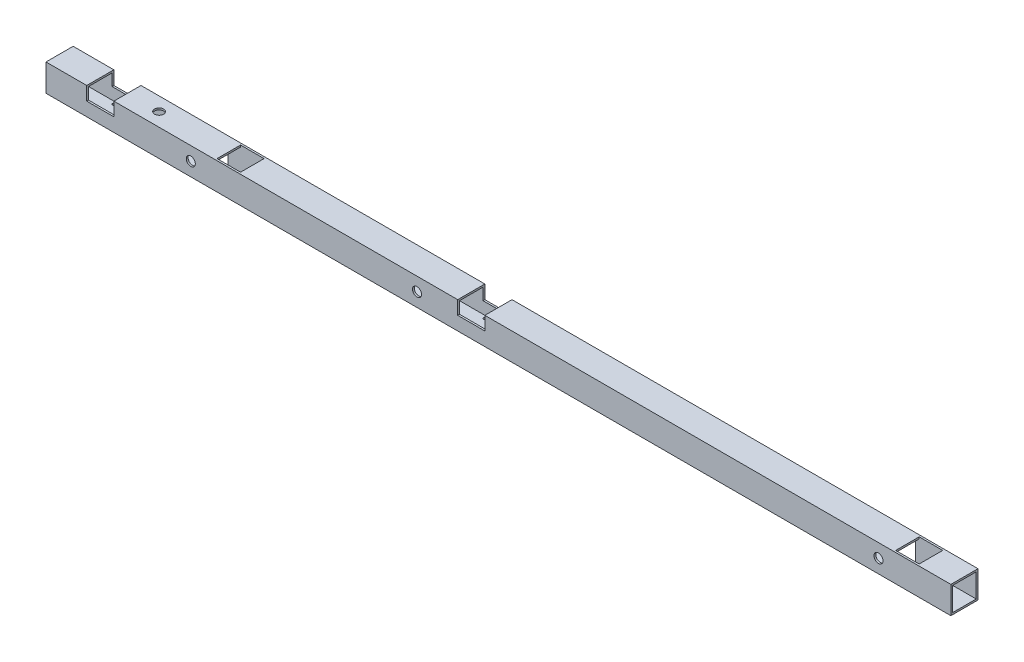
SolidWorks part; units mm, degrees
ref_plane "前视基准面" through (0, 0, 0) normal (0, 0, 1) x (1, 0, 0)
ref_plane "上视基准面" through (0, 0, 0) normal (0, 1, 0) x (1, 0, 0)
ref_plane "右视基准面" through (0, 0, 0) normal (1, 0, 0) x (0, 0, -1)
sketch "草图2" plane through (0, 0, 0) normal (1, 0, 0) x (0, 0, -1)
  line L1 (-15, 15) -> (15, 15)
  line L2 (-15, 15) -> (-15, -15)
  line L3 (-15, -15) -> (15, -15)
  line L4 (15, 15) -> (15, -15)
  line L5 (-13, -13) -> (13, -13)
  line L6 (-13, -13) -> (-13, 13)
  line L7 (-13, 13) -> (13, 13)
  line L8 (13, -13) -> (13, 13)
  line L9 (-13, -13) -> (13, 13) construction
  line L10 (-13, 13) -> (13, -13) construction
  point P4 (0, 0)
  dimension "D1" = 30
  dimension "D2" = 30
  dimension "D3" = 15
  dimension "D4" = 15
  dimension "D5" = 26
  dimension "D6" = 26
extrude "凸台-拉伸2" add sketch "草图2" along normal blind 1000 contours L7 L8 L5 L6 | L1 L4 L3 L2
sketch "草图3" plane through (0, 0, -15) normal (0, 0, -1) x (-1, 0, 0)
  line L0 (-1000, 15) -> (0, 15) construction
  line L1 (-485, 15) -> (-455, 15)
  line L2 (-485, 15) -> (-485, 0)
  line L3 (-485, 0) -> (-455, 0)
  line L4 (-455, 15) -> (-455, 0)
  line L6 (-75, 15) -> (-45, 15)
  line L7 (-75, 15) -> (-75, 0)
  line L8 (-75, 0) -> (-45, 0)
  line L9 (-45, 15) -> (-45, 0)
  line L10 (-1000, 15) -> (-1000, -15) construction
  line L11 (0, 15) -> (0, -15) construction
  point P10 (-485, 7.5)
  point P12 (-45, 7.5)
  dimension "D1" = 15
  dimension "D2" = 15
  dimension "D3" = 30
  dimension "D4" = 30
  dimension "D5" = 515
  dimension "D6" = 45
extrude "切除-拉伸1" cut sketch "草图3" against normal blind 30
sketch "草图4" plane through (0, 0, -15) normal (0, 0, -1) x (-1, 0, 0)
  line L0 (-455, 15) -> (-75, 15) construction
  line L1 (-933, 13) -> (-907, 13)
  line L2 (-933, 13) -> (-933, -13)
  line L3 (-933, -13) -> (-907, -13)
  line L4 (-907, 13) -> (-907, -13)
  line L5 (-423, 13) -> (-397, 13)
  line L6 (-423, 13) -> (-423, -13)
  line L7 (-423, -13) -> (-397, -13)
  line L8 (-397, 13) -> (-397, -13)
  line L9 (-173, 13) -> (-147, 13)
  line L10 (-173, 13) -> (-173, -13)
  line L11 (-173, -13) -> (-147, -13)
  line L12 (-147, 13) -> (-147, -13)
  line L13 (-876, 6) -> (-865, 6)
  line L14 (-876, 6) -> (-876, -6)
  line L15 (-876, -6) -> (-865, -6)
  line L16 (-865, 6) -> (-865, -6)
  line L17 (-1000, 15) -> (-485, 15) construction
  line L18 (-485, 15) -> (-485, 0) construction
  line L19 (-455, 0) -> (-455, 15) construction
  point P16 (-876, 0)
  point P25 (-455, 7.5)
  dimension "D1" = 26
  dimension "D2" = 26
  dimension "D3" = 11
  dimension "D4" = 12
  dimension "D5" = 26
  dimension "D6" = 26
  dimension "D7" = 2
  dimension "D8" = 26
  dimension "D9" = 26
  dimension "D10" = 2
  dimension "D11" = 2
  dimension "D12" = 422
  dimension "D13" = 380
  dimension "D14" = 9
  dimension "D15" = 32
  dimension "D16" = 282
extrude "切除-拉伸2" cut sketch "草图4" against normal blind 15
sketch "草图5" plane through (0, 0, 15) normal (0, 0, 1) x (1, 0, 0)
  line L1 (1000, -15) -> (0, -15) construction
  line L2 (455, 0) -> (455, 15) construction
  line L3 (485, 15) -> (485, 0) construction
  circle A0 centre (160, 0) radius 5
  circle A1 centre (410, 0) radius 5
  circle A2 centre (920, 0) radius 5
  dimension "D1" = 10
  dimension "D2" = 10
  dimension "D3" = 10
  dimension "D4" = 15
  dimension "D5" = 15
  dimension "D6" = 15
  dimension "D7" = 295
  dimension "D8" = 435
  dimension "D9" = 45
extrude "切除-拉伸3" cut sketch "草图5" against normal blind 15
sketch "草图6" plane through (0, -15, 0) normal (0, -1, 0) x (1, 0, 0)
  line L0 (1000, 15) -> (0, 15) construction
  line L1 (45, 15) -> (75, 15)
  line L2 (45, 15) -> (45, -15)
  line L3 (45, -15) -> (75, -15)
  line L4 (75, 15) -> (75, -15)
  line L5 (1000, -15) -> (0, -15) construction
  line L6 (0, 15) -> (0, -15) construction
  line L7 (455, 15) -> (485, 15)
  line L8 (455, 15) -> (455, -15)
  line L9 (455, -15) -> (485, -15)
  line L10 (485, 15) -> (485, -15)
  line L11 (1000, 15) -> (1000, -15) construction
  circle A0 centre (50, 10) radius 1.5
  circle A1 centre (70, 10) radius 1.5
  circle A2 centre (50, -10) radius 1.5
  circle A3 centre (70, -10) radius 1.5
  circle A4 centre (460, 10) radius 1.5
  circle A5 centre (480, 10) radius 1.5
  circle A6 centre (460, -10) radius 1.5
  circle A7 centre (480, -10) radius 1.5
  dimension "D5" = 3
  dimension "D6" = 3
  dimension "D7" = 3
  dimension "D8" = 3
  dimension "D17" = 3
  dimension "D18" = 3
  dimension "D19" = 3
  dimension "D20" = 3
  dimension "D1" = 30
  dimension "D2" = 30
  dimension "D3" = 45
  dimension "D4" = 515
  dimension "D9" = 5
  dimension "D10" = 5
  dimension "D11" = 5
  dimension "D12" = 5
  dimension "D13" = 5
  dimension "D14" = 5
  dimension "D15" = 5
  dimension "D16" = 5
  dimension "D21" = 5
  dimension "D22" = 5
  dimension "D23" = 5
  dimension "D24" = 5
  dimension "D25" = 5
  dimension "D26" = 5
  dimension "D27" = 5
  dimension "D28" = 5
extrude "切除-拉伸4" cut sketch "草图6" against normal blind 15 contours A6 | A7 | A5 | A4 | A3 | A2 | A1 | A0
sketch "草图8" plane through (0, 15, 0) normal (0, 1, 0) x (1, 0, 0)
  line L0 (1000, 15) -> (485, 15) construction
  line L1 (937, 13) -> (963, 13)
  line L2 (937, 13) -> (937, -13)
  line L3 (937, -13) -> (963, -13)
  line L4 (963, 13) -> (963, -13)
  line L5 (485, -15) -> (485, 15) construction
  line L6 (455, 15) -> (75, 15) construction
  line L7 (187, 13) -> (213, 13)
  line L8 (187, 13) -> (187, -13)
  line L9 (187, -13) -> (213, -13)
  line L10 (213, 13) -> (213, -13)
  line L11 (455, -15) -> (455, 15) construction
  line L12 (455, -15) -> (75, -15) construction
  circle A0 centre (110, 0) radius 5
  point P14 (213, 0)
  dimension "D9" = 10
  dimension "D1" = 26
  dimension "D2" = 26
  dimension "D3" = 2
  dimension "D4" = 452
  dimension "D5" = 26
  dimension "D6" = 26
  dimension "D7" = 2
  dimension "D8" = 242
  dimension "D10" = 345
  dimension "D11" = 15
extrude "切除-拉伸5" cut sketch "草图8" against normal blind 15
sketch "草图9" plane through (0, -15, 0) normal (0, -1, 0) x (1, 0, 0)
  line L0 (1000, 15) -> (0, 15) construction
  line L1 (45, 15) -> (75, 15)
  line L2 (45, 15) -> (45, -15)
  line L3 (45, -15) -> (75, -15)
  line L4 (75, 15) -> (75, -15)
  line L5 (1000, -15) -> (0, -15) construction
  line L6 (0, 15) -> (0, -15) construction
  line L7 (455, 15) -> (485, 15)
  line L8 (455, 15) -> (455, -15)
  line L9 (455, -15) -> (485, -15)
  line L10 (485, 15) -> (485, -15)
  line L11 (1000, 15) -> (1000, -15) construction
  line L13 (97, 13) -> (123, 13)
  line L14 (97, 13) -> (97, -13)
  line L15 (97, -13) -> (123, -13)
  line L16 (123, 13) -> (123, -13)
  circle A0 centre (950, 0) radius 5
  circle A1 centre (200, 0) radius 5
  point P12 (45, 0)
  dimension "D5" = 10
  dimension "D7" = 10
  dimension "D1" = 30
  dimension "D2" = 30
  dimension "D3" = 45
  dimension "D4" = 515
  dimension "D6" = 465
  dimension "D8" = 255
  dimension "D9" = 15
  dimension "D10" = 26
  dimension "D11" = 26
  dimension "D12" = 2
  dimension "D13" = 332
extrude "切除-拉伸6" cut sketch "草图9" against normal blind 15 contours A0 | A1 | L13 L16 L15 L14
